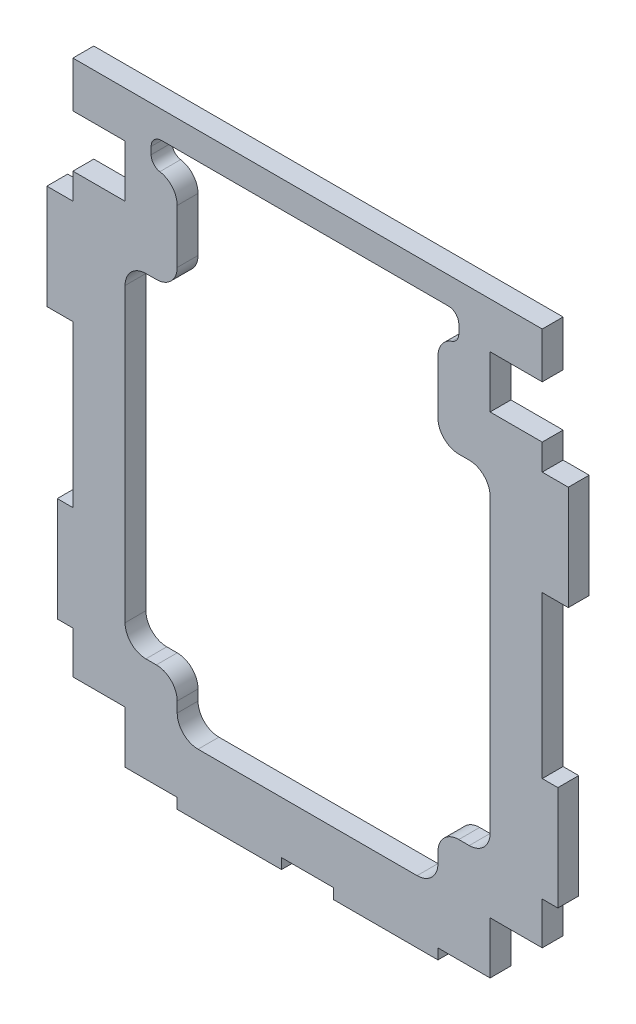
SolidWorks part; units mm, degrees
ref_plane "前视基准面" through (0, 0, 0) normal (0, 0, 1) x (1, 0, 0)
ref_plane "上视基准面" through (0, 0, 0) normal (0, 1, 0) x (1, 0, 0)
ref_plane "右视基准面" through (0, 0, 0) normal (1, 0, 0) x (0, 0, -1)
sketch "Model" plane through (0, 0, 0) normal (0, 0, 1) x (1, 0, 0)
  line L0 (1047.9126, 680.4577) -> (1047.9126, 676.0685)
  line L1 (1047.9126, 671.0685) -> (1047.9126, 668.5732)
  line L2 (1047.9126, 658.5732) -> (1047.9126, 643.1283)
  line L3 (1047.9126, 633.1283) -> (1047.9126, 629.0685)
  line L4 (1047.9126, 643.1283) -> (1046.4126, 643.1283)
  line L5 (1047.9126, 633.1283) -> (1046.4126, 633.1283)
  line L6 (1047.9126, 629.0685) -> (1052.9126, 629.0685)
  line L7 (1052.9126, 629.0685) -> (1052.9126, 624.0685)
  line L8 (1047.9126, 676.0685) -> (1052.9126, 676.0685)
  line L9 (1052.9126, 676.0685) -> (1052.9126, 671.0685)
  line L10 (1052.9126, 671.0685) -> (1047.9126, 671.0685)
  line L11 (1046.4126, 643.1283) -> (1046.4126, 633.1283)
  line L12 (1092.9126, 680.4577) -> (1047.9126, 680.4577)
  line L13 (1072.9126, 624.0685) -> (1067.9126, 624.0685)
  line L14 (1057.9126, 624.0685) -> (1052.9126, 624.0685)
  line L15 (1067.9126, 623.0685) -> (1057.9126, 623.0685)
  line L16 (1057.9126, 624.0685) -> (1057.9126, 623.0685)
  line L17 (1067.9126, 623.0685) -> (1067.9126, 624.0685)
  line L18 (1057.9126, 668.0685) -> (1057.9126, 673.2185)
  line L19 (1055.9126, 666.0685) -> (1054.9126, 666.0685)
  line L20 (1057.9126, 631.0685) -> (1057.9126, 632.0685)
  line L21 (1055.9126, 634.0685) -> (1054.9126, 634.0685)
  line L22 (1059.9126, 629.0685) -> (1080.9126, 629.0685)
  line L23 (1056.4126, 677.8676) -> (1083.9126, 677.8676)
  line L24 (1092.9126, 680.4577) -> (1092.9126, 676.0685)
  line L25 (1092.9126, 671.0685) -> (1092.9126, 668.5732)
  line L26 (1092.9126, 658.5732) -> (1092.9126, 643.1283)
  line L27 (1092.9126, 633.1283) -> (1092.9126, 629.0685)
  line L28 (1092.9126, 643.1283) -> (1094.4126, 643.1283)
  line L29 (1092.9126, 633.1283) -> (1094.4126, 633.1283)
  line L30 (1092.9126, 668.5732) -> (1095.4126, 668.5732)
  line L31 (1092.9126, 658.5732) -> (1095.4126, 658.5732)
  line L32 (1092.9126, 629.0685) -> (1087.9126, 629.0685)
  line L33 (1087.9126, 629.0685) -> (1087.9126, 624.0685)
  line L34 (1092.9126, 676.0685) -> (1087.9126, 676.0685)
  line L35 (1087.9126, 676.0685) -> (1087.9126, 671.0685)
  line L36 (1087.9126, 671.0685) -> (1092.9126, 671.0685)
  line L37 (1094.4126, 643.1283) -> (1094.4126, 633.1283)
  line L38 (1082.9126, 624.0685) -> (1087.9126, 624.0685)
  line L39 (1072.9126, 623.0685) -> (1082.9126, 623.0685)
  line L40 (1082.9126, 624.0685) -> (1082.9126, 623.0685)
  line L41 (1072.9126, 623.0685) -> (1072.9126, 624.0685)
  line L42 (1082.9126, 668.0685) -> (1082.9126, 673.2185)
  line L43 (1084.9126, 666.0685) -> (1085.9126, 666.0685)
  line L44 (1082.9126, 631.0685) -> (1082.9126, 632.0685)
  line L45 (1084.9126, 634.0685) -> (1085.9126, 634.0685)
  line L46 (1087.9126, 664.0685) -> (1087.9126, 636.0685)
  line L47 (1052.9126, 664.0685) -> (1052.9126, 636.0685)
  line L48 (1095.4126, 668.5732) -> (1095.4126, 658.5732)
  line L49 (1047.9126, 668.5732) -> (1045.4126, 668.5732)
  line L50 (1045.4126, 668.5732) -> (1045.4126, 658.5732)
  line L51 (1045.4126, 658.5732) -> (1047.9126, 658.5732)
  line L52 (1084.9126, 676.047) -> (1084.9126, 676.8676)
  line L53 (1055.4126, 676.1766) -> (1055.4126, 676.8676)
  arc A0 (1052.9126, 636.0685) -> (1054.9126, 634.0685) centre (1054.9126, 636.0685) ccw
  arc A1 (1054.9126, 666.0685) -> (1052.9126, 664.0685) centre (1054.9126, 664.0685) ccw
  arc A2 (1057.9126, 673.2185) -> (1056.2459, 675.1906) centre (1055.9126, 673.2185) ccw
  arc A3 (1055.4126, 676.1766) -> (1056.2459, 675.1906) centre (1056.4126, 676.1766) ccw
  arc A4 (1055.9126, 666.0685) -> (1057.9126, 668.0685) centre (1055.9126, 668.0685) ccw
  arc A5 (1057.9126, 631.0685) -> (1059.9126, 629.0685) centre (1059.9126, 631.0685) ccw
  arc A6 (1057.9126, 632.0685) -> (1055.9126, 634.0685) centre (1055.9126, 632.0685) ccw
  arc A7 (1056.4126, 677.8676) -> (1055.4126, 676.8676) centre (1056.4126, 676.8676) ccw
  arc A8 (1085.9126, 634.0685) -> (1087.9126, 636.0685) centre (1085.9126, 636.0685) ccw
  arc A9 (1087.9126, 664.0685) -> (1085.9126, 666.0685) centre (1085.9126, 664.0685) ccw
  arc A10 (1084.2459, 675.1042) -> (1082.9126, 673.2185) centre (1084.9126, 673.2185) ccw
  arc A11 (1084.2459, 675.1042) -> (1084.9126, 676.047) centre (1083.9126, 676.047) ccw
  arc A12 (1082.9126, 668.0685) -> (1084.9126, 666.0685) centre (1084.9126, 668.0685) ccw
  arc A13 (1080.9126, 629.0685) -> (1082.9126, 631.0685) centre (1080.9126, 631.0685) ccw
  arc A14 (1084.9126, 634.0685) -> (1082.9126, 632.0685) centre (1084.9126, 632.0685) ccw
  arc A15 (1084.9126, 676.8676) -> (1083.9126, 677.8676) centre (1083.9126, 676.8676) ccw
extrude "凸台-拉伸1" add sketch "Model" along normal blind 2
